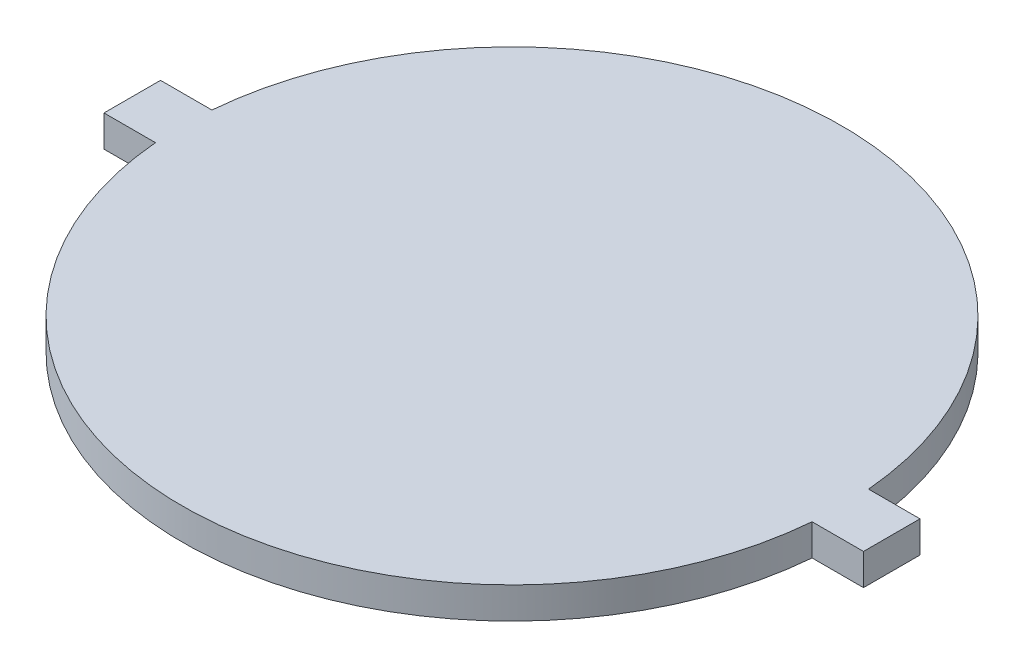
SolidWorks part; units mm, degrees
ref_plane "Front Plane" through (0, 0, 0) normal (0, 0, 1) x (1, 0, 0)
ref_plane "Top Plane" through (0, 0, 0) normal (0, 1, 0) x (1, 0, 0)
ref_plane "Right Plane" through (0, 0, 0) normal (1, 0, 0) x (0, 0, -1)
sketch "Sketch3" plane through (0, 0, 0) normal (0, 1, 0) x (1, 0, 0)
  circle A0 centre (0, 0) radius 52.5
  dimension "D1" = 105
extrude "Boss-Extrude1" add sketch "Sketch3" along normal blind 5
ref_plane "Plane1" through (0, 2.5, 0) normal (0, 1, 0) x (1, 0, 0)
sketch "Sketch5" plane through (0, 2.5, 0) normal (0, 1, 0) x (1, 0, 0)
  line L1 (44.5, 4.5) -> (60.5, 4.5)
  line L2 (44.5, 4.5) -> (44.5, -4.5)
  line L3 (44.5, -4.5) -> (60.5, -4.5)
  line L4 (60.5, 4.5) -> (60.5, -4.5)
  line L5 (44.5, 4.5) -> (60.5, -4.5) construction
  line L6 (44.5, -4.5) -> (60.5, 4.5) construction
  line L7 (-60.5, 4.5) -> (-44.5, 4.5)
  line L8 (-60.5, 4.5) -> (-60.5, -4.5)
  line L9 (-60.5, -4.5) -> (-44.5, -4.5)
  line L10 (-44.5, 4.5) -> (-44.5, -4.5)
  line L11 (-60.5, 4.5) -> (-44.5, -4.5) construction
  line L12 (-60.5, -4.5) -> (-44.5, 4.5) construction
  circle A0 centre (0, 0) radius 52.5 construction
  point P0 (52.5, 0)
  point P7 (-52.5, 0)
  dimension "D1" = 16
  dimension "D2" = 16
  dimension "D3" = 9
  dimension "D4" = 9
extrude "Boss-Extrude2" add sketch "Sketch5" along normal mid plane 5
